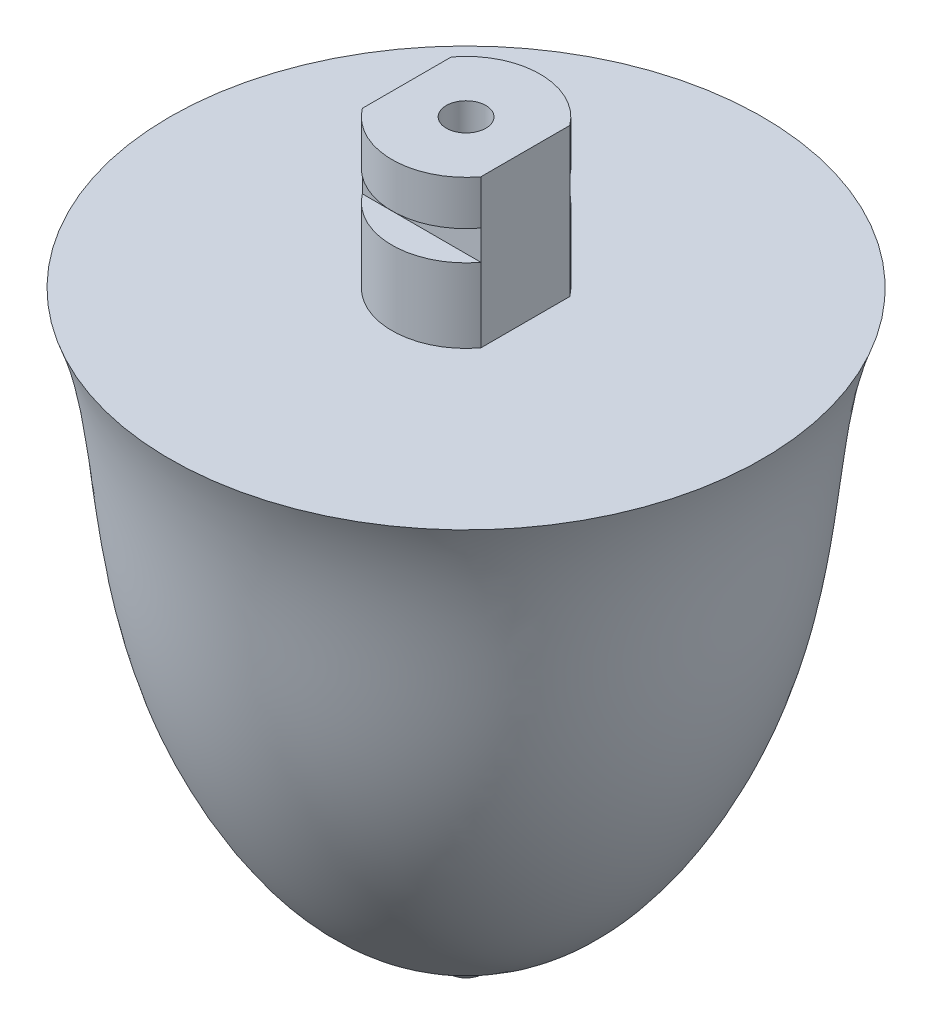
SolidWorks part; units mm, degrees
material "ABS"
ref_plane "Front" through (0, 0, 0) normal (0, 0, 1) x (1, 0, 0)
ref_plane "Top" through (0, 0, 0) normal (0, 1, 0) x (1, 0, 0)
ref_plane "Right" through (0, 0, 0) normal (1, 0, 0) x (0, 0, -1)
sketch "Sketch1" plane through (0, 0, 0) normal (0, 0, 1) x (1, 0, 0)
  line L0 (0, 0) -> (0, -120) construction
  line L5 (0, 0) -> (60, 0)
  line L7 (0, 0) -> (0, -120)
  arc A2 (13.0773, -110) -> (5.3316, -116.4065) centre (17.7581, -123.545) ccw
  arc A3 (5.3316, -116.4065) -> (0, -120) centre (-0.9946, -112.7725) cw
  spline S0 degree 3 poles (13.0773, -110) (26.4415, -105.3816) (58.4, -57.5711) (51.5987, -21.7946) (60, 0) knots 0.017668 0.017668 0.017668 0.017668 0.353401 1 1 1 1
  dimension "D2" = 110
  dimension "D1" = 120
  dimension "D3" = 60
revolve "Revolve5" add sketch "Sketch1" angle 360 about L0
sketch "Sketch2" plane through (0, 0, 0) normal (0, 1, 0) x (1, 0, 0)
  line L0 (60, 0) -> (-60, 0) construction
  line L1 (12, 9) -> (12, -9)
  line L2 (-12, 9) -> (-12, -9)
  line L3 (12, -9) -> (-12, -9) construction
  line L4 (-12, 9) -> (12, 9) construction
  arc A0 (-12, -9) -> (12, -9) centre (0, 0) ccw
  circle A1 centre (0, 0) radius 60 construction
  arc A4 (12, 9) -> (-12, 9) centre (0, 0) ccw
  dimension "D1" = 30
  dimension "D2" = 12
  dimension "D3" = 12
extrude "Boss-Extrude1" add sketch "Sketch2" along normal blind 30
sketch "Sketch3" plane through (0, 30, 0) normal (0, 1, 0) x (1, 0, 0)
  circle A0 centre (0, 0) radius 4
  dimension "D1" = 8
extrude "Cut-Extrude1" cut sketch "Sketch3" against normal blind 30
ref_plane "Plane1" through (0, 0, 9) normal (0, 0, 1) x (1, 0, 0)
sketch "Sketch5" plane through (0, 0, 9) normal (0, 0, 1) x (1, 0, 0)
  line L0 (-12, 30) -> (-12, 0) construction
  line L1 (-12, 21) -> (12, 21)
  line L2 (-12, 21) -> (-12, 15)
  line L3 (-12, 15) -> (12, 15)
  line L4 (12, 21) -> (12, 15)
  line L5 (12, 30) -> (12, 0) construction
  dimension "D1" = 6
extrude "Cut-Extrude2" cut sketch "Sketch5" along normal up to next
mirror "Mirror1" about plane through (0, 0, 0) normal (0, 0, 1) of "Cut-Extrude2"
